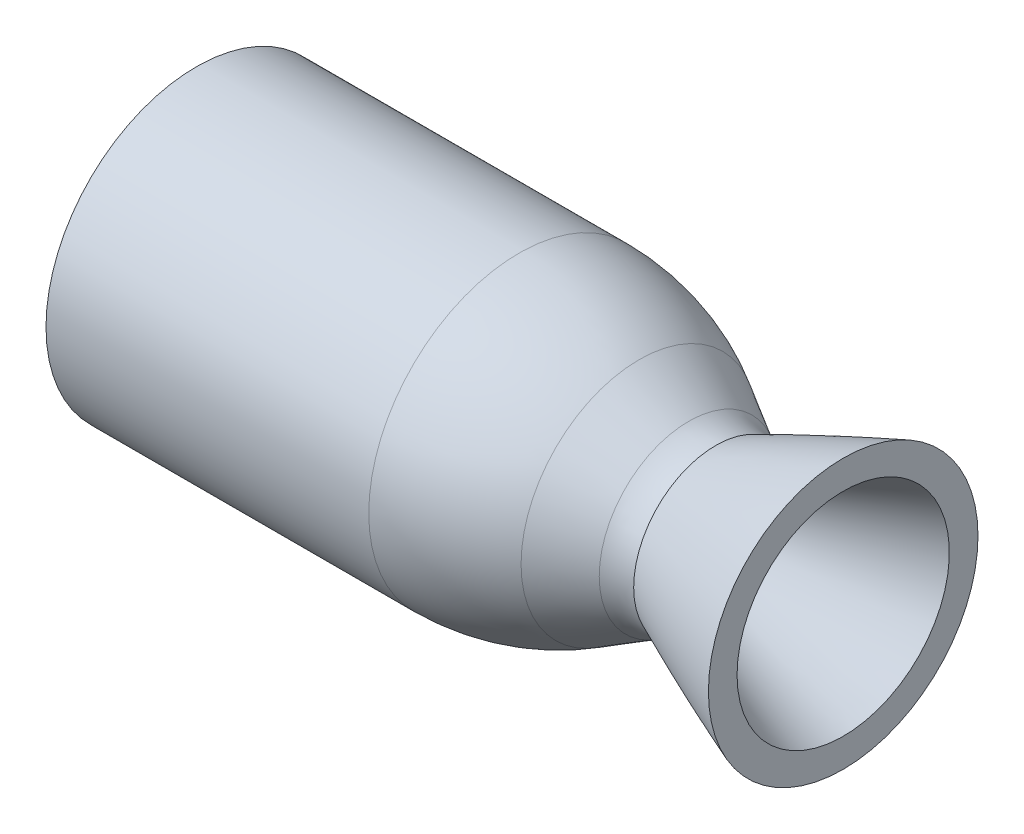
SolidWorks part; units mm, degrees
material "Copper"
ref_plane "Front" through (0, 0, 0) normal (0, 0, 1) x (1, 0, 0)
ref_plane "Top" through (0, 0, 0) normal (0, 1, 0) x (1, 0, 0)
ref_plane "Right" through (0, 0, 0) normal (1, 0, 0) x (0, 0, -1)
sketch "Sketch1" plane through (0, 0, 0) normal (0, 0, 1) x (1, 0, 0)
  line L0 (192.877, 42.655) -> (215.1271, 29.8089) construction
  line L1 (0, 55.5012) -> (144.9347, 55.5012) construction
  line L2 (192.877, 42.655) -> (215.1271, 29.8089)
  line L3 (0, 55.5012) -> (144.9347, 55.5012)
  line L4 (0, 67.5012) -> (144.9347, 67.5012)
  line L5 (198.877, 53.0473) -> (221.1272, 40.2012)
  line L6 (0, 67.5012) -> (0, 55.5012)
  line L7 (370.4363, 74.9571) -> (370.4363, 87.4632)
  line L9 (0, 0) -> (345.8568, 0) construction
  line L10 (0, 0) -> (370.4363, 0) construction
  line L11 (367.0572, 86.4715) -> (370.4363, 87.4632)
  arc A0 (233.7428, 24.8208) -> (237.5976, 25.6398) centre (233.7428, 34.3024) ccw construction
  arc A1 (215.1271, 29.8089) -> (233.7428, 24.8208) centre (233.7428, 62.0521) ccw construction
  arc A2 (192.877, 42.655) -> (144.9347, 55.5012) centre (144.9346, -40.3836) ccw construction
  arc A3 (233.7428, 24.8208) -> (237.5976, 25.6398) centre (233.7428, 34.3024) ccw
  arc A4 (215.1271, 29.8089) -> (233.7428, 24.8208) centre (233.7428, 62.0521) ccw
  arc A5 (192.877, 42.655) -> (144.9347, 55.5012) centre (144.9346, -40.3836) ccw
  arc A6 (198.877, 53.0473) -> (144.9347, 67.5012) centre (144.9346, -40.3836) ccw
  arc A7 (221.1272, 40.2012) -> (233.2202, 36.8262) centre (233.7428, 62.0521) ccw
  arc A8 (233.2202, 36.8262) -> (233.2202, 36.8262) centre (233.2202, 36.8262) ccw
  parabola Q0 (237.5976, 25.6398) -> (370.4363, 74.9571) focus (662.3735, -169.4319) apex (740.9638, 82.0231) construction
  parabola Q1 (237.5976, 25.6398) -> (370.4363, 74.9571) focus (662.3735, -169.4319) apex (740.9638, 82.0231)
  spline S0 degree 1 poles (233.2202, 36.8262) (367.0572, 86.4715) knots 0 0 1 1 construction
  spline S1 degree 3 poles (233.2202, 36.8262) (236.0691, 38.0925) (241.7895, 40.6095) (253.1625, 45.511) (267.3246, 51.4218) (284.2096, 58.1588) (300.9914, 64.5424) (317.6682, 70.5714) (334.242, 76.2463) (347.9631, 80.6787) (358.8959, 84.0494) (364.3304, 85.6713) (367.0572, 86.4715) knots 0.492865 0.492865 0.492865 0.492865 0.492973 0.49308 0.493295 0.49351 0.493725 0.49394 0.494155 0.49437 0.494478 0.494585 0.494585 0.494585 0.494585
  dimension "D1" = 12
revolve "Revolve1" add sketch "Sketch1" angle 360 about L9
ref_plane "Plane1" through (0, 100, 0) normal (0, 1, 0) x (1, 0, 0)
sketch "Sketch3" plane through (0, 100, 0) normal (0, 1, 0) x (1, 0, 0)
  line L1 (0, 1) -> (370.1547, 1)
  line L2 (0, 1) -> (0, -1)
  line L3 (0, -1) -> (370.1547, -1)
  line L4 (370.1547, 1) -> (370.1547, -1)
  point P4 (0, 0)
  dimension "D1" = 2
extrude "Boss-Extrude1" [suppressed] add sketch "Sketch3" against normal up to body separate body
pattern_circular "CirPattern1" [suppressed] count 23 over 360 about axis through (0, 0, 0) along (1, 0, 0)
sketch "Sketch6" plane through (0, 0, 0) normal (0, 0, 1) x (1, 0, 0)
  line L0 (290.486, -74.3446) -> (290.486, 74.3446) construction
  line L1 (290.486, -74.3446) -> (290.486, 74.3446) construction
  line L2 (290.486, 74.3446) -> (286.041, 74.3446) construction
  line L3 (290.486, 149.3446) -> (430.486, 149.3446)
  line L4 (290.486, 149.3446) -> (290.486, -149.3446)
  line L5 (290.486, -149.3446) -> (430.486, -149.3446)
  line L6 (430.486, 149.3446) -> (430.486, -149.3446)
  point P6 (290.486, 0)
  point P7 (290.486, 0)
  dimension "D1" = 75
  dimension "D2" = 140
extrude "Cut-Extrude1" cut sketch "Sketch6" against normal through all both and the other way through all
sketch "Sketch7" [suppressed] plane through (0, 0, 0) normal (0, 0, 1) x (1, 0, 0)
  line L14 (367.3388, 85.512) -> (365.9309, 90.3097)
  line L15 (223.1271, 43.6653) -> (200.877, 56.5114)
  line L16 (144.9346, 71.5012) -> (0, 71.5012)
  line L17 (0, 71.5012) -> (0, 66.5012)
  line L18 (0, 66.5012) -> (144.9347, 66.5012)
  line L19 (198.377, 52.1813) -> (220.6272, 39.3352)
  line L24 (0, 66.5012) -> (144.9347, 66.5012)
  line L25 (198.377, 52.1813) -> (220.6272, 39.3352)
  line L27 (0, 0) -> (120.5414, 0) construction
  line L29 (367.3388, 120) -> (0, 120)
  line L30 (0, 120) -> (0, 66.5012)
  line L31 (367.3388, 120) -> (367.3388, 85.512)
  line L32 (290.486, 100) -> (0, 100) construction
  arc A4 (220.6272, 39.3352) -> (233.4246, 35.8228) centre (233.7428, 62.0521) ccw
  arc A5 (223.1271, 43.6653) -> (232.4488, 40.8603) centre (233.7428, 62.0521) ccw
  arc A6 (200.877, 56.5114) -> (144.9346, 71.5012) centre (144.9346, -40.3836) ccw
  arc A7 (198.377, 52.1813) -> (144.9347, 66.5012) centre (144.9346, -40.3836) ccw
  arc A8 (220.6272, 39.3352) -> (233.4246, 35.8228) centre (233.7428, 62.0521) ccw
  arc A11 (198.377, 52.1813) -> (144.9347, 66.5012) centre (144.9346, -40.3836) ccw
  spline S2 degree 3 poles (1167.797, 392.1019) (-3.1068, -88.355) (129.489, -8.9342) (253.1278, 44.4104) (267.3317, 50.3449) (284.2656, 57.1077) (301.0951, 63.5146) (317.8184, 69.5644) (334.4373, 75.2577) (348.195, 79.7034) (450.9963, 111.4039) (538.1638, 121.2677) (1338.3734, 324.3706) knots 0.488613 0.488613 0.488613 0.488613 0.492967 0.493075 0.493291 0.493506 0.493722 0.493938 0.494154 0.494369 0.494477 0.498201 0.498201 0.498201 0.498201 only from (233.4246, 35.8228) to (367.3388, 85.512)
  spline S3 degree 3 poles (1337.1181, 328.6141) (538.338, 126.375) (450.2735, 116.4134) (346.6856, 84.4703) (332.8577, 80.0019) (316.157, 74.2806) (299.3545, 68.2021) (282.4482, 61.766) (265.44, 54.9735) (251.1762, 49.0139) (126.6044, -4.7332) (-6.7831, -84.7443) (1167.0035, 396.6596) knots 0.48925 0.48925 0.48925 0.48925 0.492984 0.493092 0.493308 0.493523 0.493739 0.493955 0.494171 0.494386 0.494494 0.498864 0.498864 0.498864 0.498864 only from (365.9309, 90.3097) to (232.4488, 40.8603)
  spline S4 degree 3 poles (6695.7596, 2723.2734) (-208.5158, -222.3234) (41.7487, -46.7902) (253.1278, 44.4104) (267.3317, 50.3449) (284.2656, 57.1077) (301.0951, 63.5146) (317.8184, 69.5644) (334.4373, 75.2577) (348.195, 79.7034) (551.019, 142.2476) (706.6145, 120.262) (7135.3733, 1869.4169) knots 0.485293 0.485293 0.485293 0.485293 0.492967 0.493075 0.493291 0.493506 0.493722 0.493938 0.494154 0.494369 0.494477 0.502139 0.502139 0.502139 0.502139 only from (233.4246, 35.8228) to (367.3388, 85.512) construction
  spline S5 degree 3 poles (233.4246, 35.8228) (236.1831, 37.0494) (241.8202, 39.5317) (253.1278, 44.4104) (267.3317, 50.3449) (284.2656, 57.1077) (301.0951, 63.5146) (317.8184, 69.5644) (334.4373, 75.2577) (348.195, 79.7034) (359.1564, 83.0835) (364.605, 84.7097) (367.3388, 85.512) knots 0.492863 0.492863 0.492863 0.492863 0.492967 0.493075 0.493291 0.493506 0.493722 0.493938 0.494154 0.494369 0.494477 0.494585 0.494585 0.494585 0.494585
  dimension "D1" = 20
  dimension "D2" = 0
revolve "Cut-Revolve3" [suppressed] cut sketch "Sketch7" angle 360 about L27
sketch "Sketch10" plane through (0, 0, 0) normal (0, 0, 1) x (1, 0, 0)
  line L0 (251.8563, 43.8404) -> (251.8563, 44.927)
  line L1 (256.2863, 45.7137) -> (262.9245, 49.5634)
  line L2 (0, 0) -> (71.6518, 0) construction
  line L9 (254.3695, 50.3267) -> (256.2881, 45.7095)
  line L10 (256.2881, 45.7095) -> (265.5225, 49.5467)
  line L11 (265.5225, 49.5467) -> (263.6039, 54.1639)
  line L12 (254.3695, 50.3267) -> (256.2863, 45.7137) construction
  line L15 (237.9459, 43.2767) -> (239.9271, 38.686)
  line L16 (251.8586, 43.8352) -> (249.8774, 48.4259)
  line L17 (239.9271, 38.686) -> (251.8586, 43.8352)
  line L19 (251.8563, 43.8404) -> (249.8774, 48.4259) construction
  arc A3 (263.6039, 54.1639) -> (254.3695, 50.3267) centre (258.9867, 52.2453) ccw
  arc A5 (249.8774, 48.4259) -> (237.9459, 43.2767) centre (243.9116, 45.8513) ccw
  spline S0 degree 3 poles (3013.8022, 1161.353) (-98.6484, -148.0484) (87.8141, -26.915) (253.1278, 44.4104) (267.3317, 50.3449) (284.2656, 57.1077) (301.0951, 63.5146) (317.8184, 69.5644) (334.4373, 75.2577) (348.195, 79.7034) (500.2574, 126.5944) (623.8062, 126.0914) (3273.4491, 829.2412) knots 0.487036 0.487036 0.487036 0.487036 0.492967 0.493075 0.493291 0.493506 0.493722 0.493938 0.494154 0.494369 0.494477 0.500141 0.500141 0.500141 0.500141 only from (233.4246, 35.8228) to (367.3388, 85.512) construction
  spline S1 degree 3 poles (251.8563, 43.8404) (253.334, 44.4688) (254.8107, 45.0932) (256.2863, 45.7137) knots 0.493095 0.493095 0.493095 0.493095 0.493151 0.493151 0.493151 0.493151
  spline S2 degree 3 poles (1167.7409, 392.7148) (-2.9762, -87.0804) (129.5464, -7.7647) (253.1625, 45.511) (267.3246, 51.4218) (284.2096, 58.1588) (300.9914, 64.5424) (317.6682, 70.5714) (334.242, 76.2463) (347.9631, 80.6787) (450.7834, 112.3795) (538.0361, 122.2692) (1338.0994, 325.3098) knots 0.488621 0.488621 0.488621 0.488621 0.492973 0.49308 0.493295 0.49351 0.493725 0.49394 0.494155 0.49437 0.494478 0.498199 0.498199 0.498199 0.498199 only from (233.2202, 36.8262) to (367.0572, 86.4715) construction
  spline S3 degree 3 poles (251.8563, 44.927) (255.5523, 46.4971) (259.2421, 48.0427) (262.9245, 49.5634) knots 0.4931 0.4931 0.4931 0.4931 0.49324 0.49324 0.49324 0.49324
  dimension "D1" = 12
  dimension "D2" = 0
  dimension "D3" = 0
revolve "Revolve2" [suppressed] add sketch "Sketch10" angle 360 about L2
sketch "Sketch11" plane through (0, 0, 0) normal (0, 0, 1) x (1, 0, 0)
  line L4 (0, 0) -> (91.6705, 0) construction
  line L5 (290.486, -74.3446) -> (290.486, 74.3446) construction
  line L6 (290.486, 60.5307) -> (290.486, 59.4599)
  line L7 (277.4096, 59.7288) -> (279.4331, 54.6781) construction
  line L8 (277.4096, 59.7288) -> (279.2673, 55.0919)
  line L9 (279.2673, 55.0919) -> (279.4309, 56.2318)
  spline S1 degree 3 poles (3013.8022, 1161.353) (-98.6484, -148.0484) (87.8141, -26.915) (253.1278, 44.4104) (267.3317, 50.3449) (284.2656, 57.1077) (301.0951, 63.5146) (317.8184, 69.5644) (334.4373, 75.2577) (348.195, 79.7034) (500.2574, 126.5944) (623.8062, 126.0914) (3273.4491, 829.2412) knots 0.487036 0.487036 0.487036 0.487036 0.492967 0.493075 0.493291 0.493506 0.493722 0.493938 0.494154 0.494369 0.494477 0.500141 0.500141 0.500141 0.500141 only from (233.4246, 35.8228) to (367.3388, 85.512) construction
  spline S3 degree 3 poles (279.2673, 55.0919) (280.9292, 55.7492) (284.673, 57.2198) (288.4091, 58.6642) (290.486, 59.4599) knots 0.493443 0.493443 0.493443 0.493443 0.493506 0.493586 0.493586 0.493586 0.493586
  spline S4 degree 3 poles (1167.7409, 392.7148) (-2.9762, -87.0804) (129.5464, -7.7647) (253.1625, 45.511) (267.3246, 51.4218) (284.2096, 58.1588) (300.9914, 64.5424) (317.6682, 70.5714) (334.242, 76.2463) (347.9631, 80.6787) (450.7834, 112.3795) (538.0361, 122.2692) (1338.0994, 325.3098) knots 0.488621 0.488621 0.488621 0.488621 0.492973 0.49308 0.493295 0.49351 0.493725 0.49394 0.494155 0.49437 0.494478 0.498199 0.498199 0.498199 0.498199 only from (233.2202, 36.8262) to (367.0572, 86.4715) construction
  spline S5 degree 3 poles (279.4309, 56.2318) (281.0195, 56.8592) (284.7087, 58.3067) (288.3905, 59.7287) (290.486, 60.5307) knots 0.49345 0.49345 0.49345 0.49345 0.49351 0.493591 0.493591 0.493591 0.493591
  dimension "D1" = 150
revolve "Revolve4" [suppressed] add sketch "Sketch11" angle 360 about L4
sketch "Sketch12" [suppressed] plane through (0, 0, 0) normal (0, 0, 1) x (1, 0, 0)
  line L2 (290.486, -59.4599) -> (290.486, 59.4599) construction
  line L3 (279.486, 55.1783) -> (279.486, 44.4178)
  line L4 (0, 66.5012) -> (144.9347, 66.5012)
  line L5 (198.377, 52.1813) -> (220.6271, 39.3352)
  line L6 (0, 66.5012) -> (144.9347, 66.5012)
  line L7 (198.377, 52.1813) -> (220.6271, 39.3352)
  arc A6 (198.377, 52.1813) -> (144.9347, 66.5012) centre (144.9346, -40.3836) ccw
  arc A7 (220.6271, 39.3352) -> (233.4246, 35.8228) centre (233.7428, 62.0521) ccw
  arc A8 (198.377, 52.1813) -> (144.9347, 66.5012) centre (144.9346, -40.3836) ccw
  arc A9 (220.6271, 39.3352) -> (233.4246, 35.8228) centre (233.7428, 62.0521) ccw
  spline S1 degree 3 poles (237.191, 26.5534) (240.0255, 27.8148) (245.7175, 30.3221) (257.0309, 35.2033) (271.115, 41.0877) (287.9003, 47.7912) (304.5764, 54.1396) (321.1412, 60.1321) (337.5967, 65.7694) (351.2137, 70.1696) (362.0602, 73.5143) (367.4501, 75.1229) (370.1547, 75.9166) knots 0.492859 0.492859 0.492859 0.492859 0.492967 0.493075 0.493291 0.493506 0.493722 0.493938 0.494154 0.494369 0.494477 0.494585 0.494585 0.494585 0.494585 construction
  spline S2 degree 3 poles (3013.932, 1160.9557) (-101.2038, -149.4049) (84.1489, -29.1781) (244.8464, 40.8377) (247.6916, 42.0645) (256.2165, 45.7016) (261.8852, 48.0685) (278.8361, 54.9908) (290.0645, 59.3683) (312.383, 67.6505) (323.473, 71.5551) (340.0004, 77.0555) (345.4914, 78.8295) (353.7057, 81.4027) (356.44, 82.2458) (503.0556, 126.7301) (625.2631, 126.2757) (3273.7385, 828.2313) knots -3.394597 -3.394597 -3.394597 -3.394597 0.0625 0.0625 0.125 0.125 0.25 0.25 0.5 0.5 0.75 0.75 0.875 0.875 0.9375 0.9375 4.236244 4.236244 4.236244 4.236244 only from (233.4246, 35.8228) to (367.3388, 85.512)
  spline S3 degree 3 poles (233.4246, 35.8228) (236.2766, 37.091) (239.1392, 38.3511) (244.8464, 40.8377) (247.6916, 42.0645) (256.2165, 45.7016) (261.8852, 48.0685) (271.528, 52.0063) (275.5114, 53.6071) (279.486, 55.1783) knots 0 0 0 0 0.0625 0.0625 0.125 0.125 0.25 0.25 0.338324 0.338324 0.338324 0.338324
  dimension "D2" = 11
  dimension "D1" = 10
